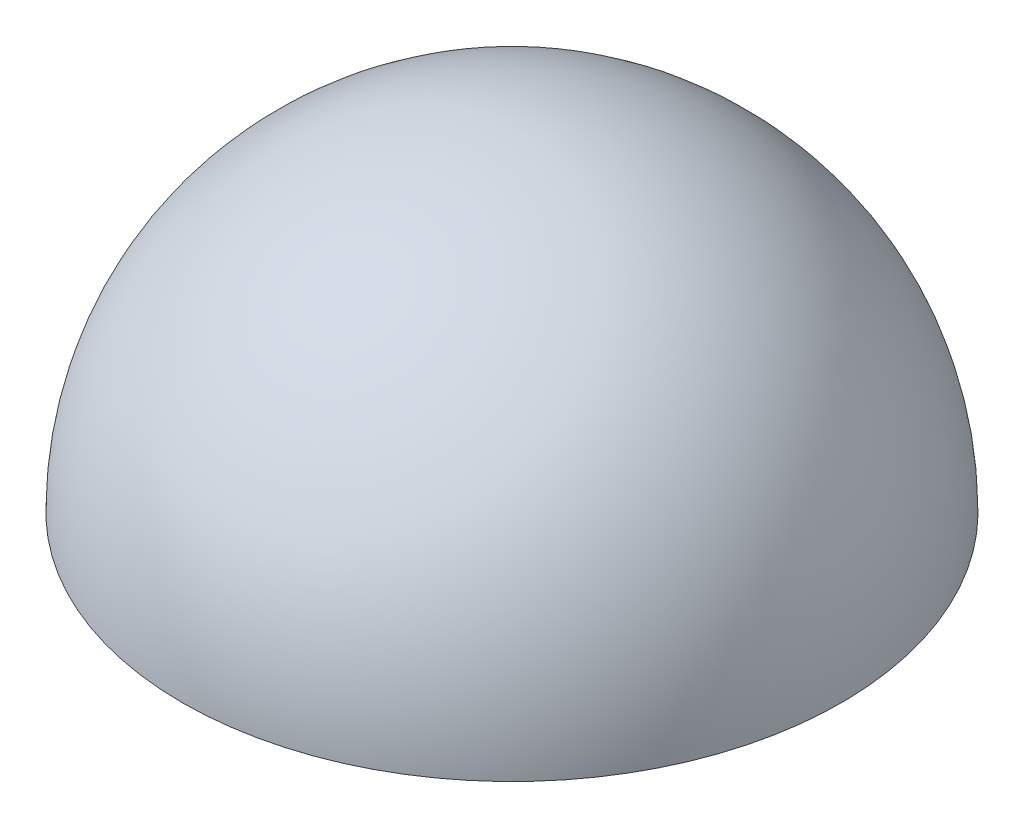
SolidWorks part; units mm, degrees
material "PMMA"
ref_plane "Front Plane" through (0, 0, 0) normal (0, 0, 1) x (1, 0, 0)
ref_plane "Top Plane" through (0, 0, 0) normal (0, 1, 0) x (1, 0, 0)
ref_plane "Right Plane" through (0, 0, 0) normal (1, 0, 0) x (0, 0, -1)
sketch "Sketch1" plane through (0, 0, 0) normal (0, 1, 0) x (1, 0, 0)
  line L0 (0, 100) -> (0, -100)
  arc A0 (0, -100) -> (0, 100) centre (0, 0) ccw
  dimension "D1" = 200
revolve "Revolve1" add sketch "Sketch1" angle 360 about L0
shell "Shell1" thickness 2
sketch "Sketch2" plane through (0, 0, 0) normal (0, 1, 0) x (1, 0, 0)
  circle A0 centre (0, 0) radius 125.7202
extrude "Cut-Extrude1" cut sketch "Sketch2" against normal blind 156
sketch "Sketch3" plane through (0, 0, 0) normal (0, -1, 0) x (-1, 0, 0)
  circle A2 centre (0, 0) radius 99
  circle A3 centre (0, 0) radius 99
  dimension "D1" = 1
extrude "Cut-Extrude2" cut sketch "Sketch3" against normal blind 4
